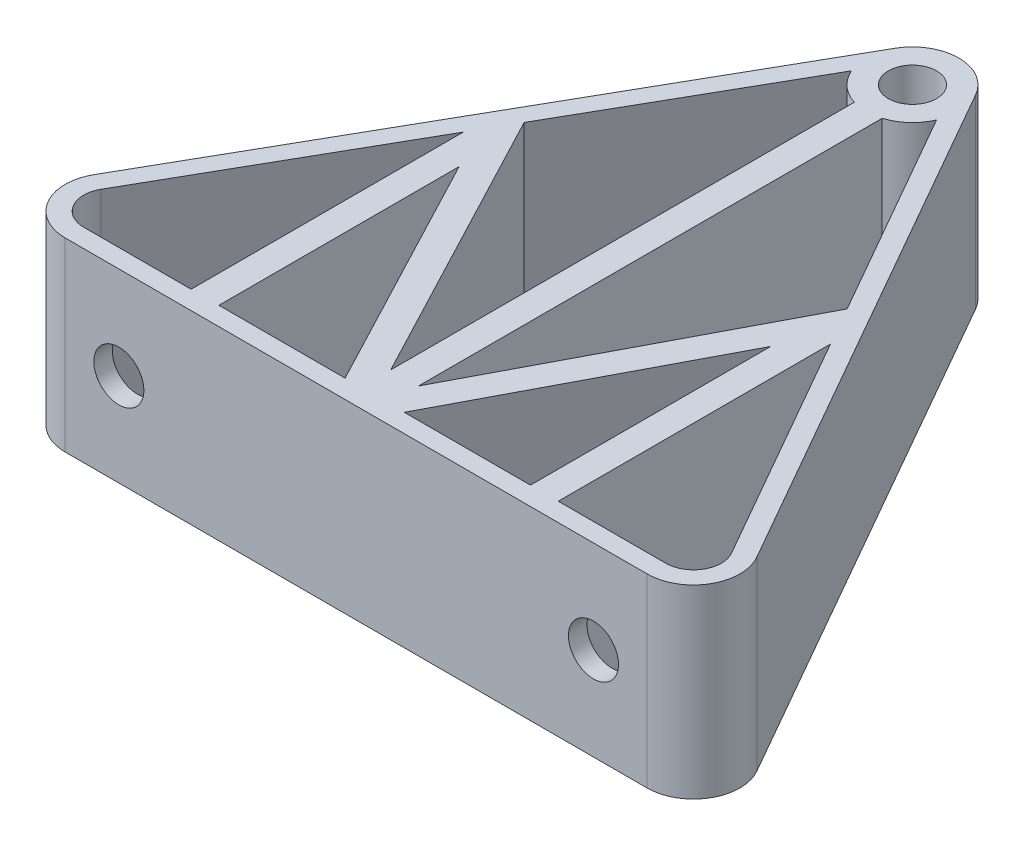
SolidWorks part; units mm, degrees
ref_plane "Alzado" through (0, 0, 0) normal (0, 0, 1) x (1, 0, 0)
ref_plane "Planta" through (0, 0, 0) normal (0, 1, 0) x (1, 0, 0)
ref_plane "Vista lateral" through (0, 0, 0) normal (1, 0, 0) x (0, 0, -1)
sketch "Croquis1" plane through (0, 0, 0) normal (0, 1, 0) x (1, 0, 0)
  line L0 (0, 0) -> (0, -60) construction
  line L1 (31.3894, -60) -> (-31.3894, -60)
  line L2 (-35.732, -52.5216) -> (-4.3425, 2.4784)
  line L3 (35.732, -52.5216) -> (4.3425, 2.4784)
  circle A0 centre (0, 0) radius 5
  arc A1 (-35.732, -52.5216) -> (-31.3894, -60) centre (-31.3894, -55) ccw
  arc A2 (35.732, -52.5216) -> (31.3894, -60) centre (31.3894, -55) cw
  point P8 (-40, -60)
  point P13 (40, -60)
  dimension "D2" = 10
  dimension "D4" = 5
  dimension "D1" = 60
  dimension "D3" = 40
extrude "Saliente-Extruir1" add sketch "Croquis1" along normal blind 20
sketch "Croquis2" plane through (0, 20, 0) normal (0, 1, 0) x (1, 0, 0)
  line L0 (0, -5) -> (0, -58) construction
  line L1 (1.5, -4.7697) -> (1.5, -58)
  line L2 (-1.5, -4.7697) -> (-1.5, -58)
  line L3 (35.732, -52.5216) -> (4.3425, 2.4784)
  line L4 (-4.3425, 2.4784) -> (-35.732, -52.5216)
  line L5 (-31.3894, -60) -> (31.3894, -60)
  line L6 (35.732, -52.5216) -> (4.3425, 2.4784)
  line L7 (-4.3425, 2.4784) -> (-35.732, -52.5216)
  line L8 (-31.3894, -60) -> (31.3894, -60)
  line L9 (-1.5, -58) -> (-18.3002, -26.013) construction
  line L10 (-18.3002, -26.013) -> (-18.3002, -58) construction
  line L11 (-17.4179, -24.467) -> (-1.5, -54.7741)
  line L12 (33.995, -53.513) -> (2.6055, 1.487)
  line L13 (-2.6055, 1.487) -> (-33.995, -53.513)
  line L14 (-31.3894, -58) -> (31.3894, -58)
  line L15 (33.995, -53.513) -> (2.6055, 1.487)
  line L16 (-2.6055, 1.487) -> (-33.995, -53.513)
  line L17 (-31.3894, -58) -> (31.3894, -58)
  line L18 (17.4179, -24.467) -> (1.5, -54.7741)
  line L19 (16.8002, -32.0948) -> (3.1943, -58)
  line L20 (-19.8002, -58) -> (-19.8002, -28.6413)
  line L21 (-16.8002, -58) -> (-16.8002, -32.0948)
  line L22 (-16.8002, -28.8689) -> (-16.8002, -28.6413)
  line L23 (-16.8002, -32.0948) -> (-3.1943, -58)
  line L24 (16.8002, -58) -> (16.8002, -32.0948)
  line L25 (19.8002, -58) -> (19.8002, -28.6413)
  arc A3 (4.3425, 2.4784) -> (-4.3425, 2.4784) centre (0, 0) ccw
  arc A4 (-35.732, -52.5216) -> (-31.3894, -60) centre (-31.3894, -55) ccw
  arc A5 (31.3894, -60) -> (35.732, -52.5216) centre (31.3894, -55) ccw
  arc A6 (4.3425, 2.4784) -> (-4.3425, 2.4784) centre (0, 0) ccw
  arc A7 (-35.732, -52.5216) -> (-31.3894, -60) centre (-31.3894, -55) ccw
  arc A8 (31.3894, -60) -> (35.732, -52.5216) centre (31.3894, -55) ccw
  circle A9 centre (0, 0) radius 2.75
  arc A10 (-4.5882, -1.987) -> (4.5882, -1.987) centre (0, 0) ccw
  arc A11 (4.3425, 2.4784) -> (-4.3425, 2.4784) centre (0, 0) ccw
  arc A12 (2.6055, 1.487) -> (-2.6055, 1.487) centre (0, 0) ccw
  arc A13 (-33.995, -53.513) -> (-31.3894, -58) centre (-31.3894, -55) ccw
  arc A14 (31.3894, -58) -> (33.995, -53.513) centre (31.3894, -55) ccw
  arc A15 (2.6055, 1.487) -> (-2.6055, 1.487) centre (0, 0) ccw
  arc A16 (-33.995, -53.513) -> (-31.3894, -58) centre (-31.3894, -55) ccw
  arc A17 (31.3894, -58) -> (33.995, -53.513) centre (31.3894, -55) ccw
  dimension "D3" = 5.5
  dimension "D4" = 10
  dimension "D5" = 1.5
  dimension "D6" = 1.5
  dimension "D7" = 1.5
  dimension "D8" = 1.5
  dimension "D1" = 0
  dimension "D2" = 2
extrude "Cortar-Extruir1" cut sketch "Croquis2" against normal blind 20 contours L16 A16 L17 L20 | L23 L21 L17 | A10 L16 L11 L2 | A10 L1 L18 L15 | L17 A17 L15 L25 | L17 L24 L19
sketch "Croquis3" plane through (0, 20, 0) normal (0, 1, 0) x (1, 0, 0)
  circle A0 centre (0, 0) radius 2.6
  dimension "D1" = 5.2
extrude "Cortar-Extruir2" cut sketch "Croquis3" against normal blind 20
sketch "Croquis4" plane through (0, 0, 58) normal (0, 0, -1) x (-1, 0, 0)
  line L0 (31.3894, 0) -> (19.8002, 20) construction
  line L1 (-19.8002, 0) -> (-31.3894, 20) construction
  circle A0 centre (25.5948, 10) radius 2.7
  circle A1 centre (-25.5948, 10) radius 2.7
  dimension "D1" = 5.4
  dimension "D2" = 5.4
extrude "Cortar-Extruir3" cut sketch "Croquis4" against normal blind 20
